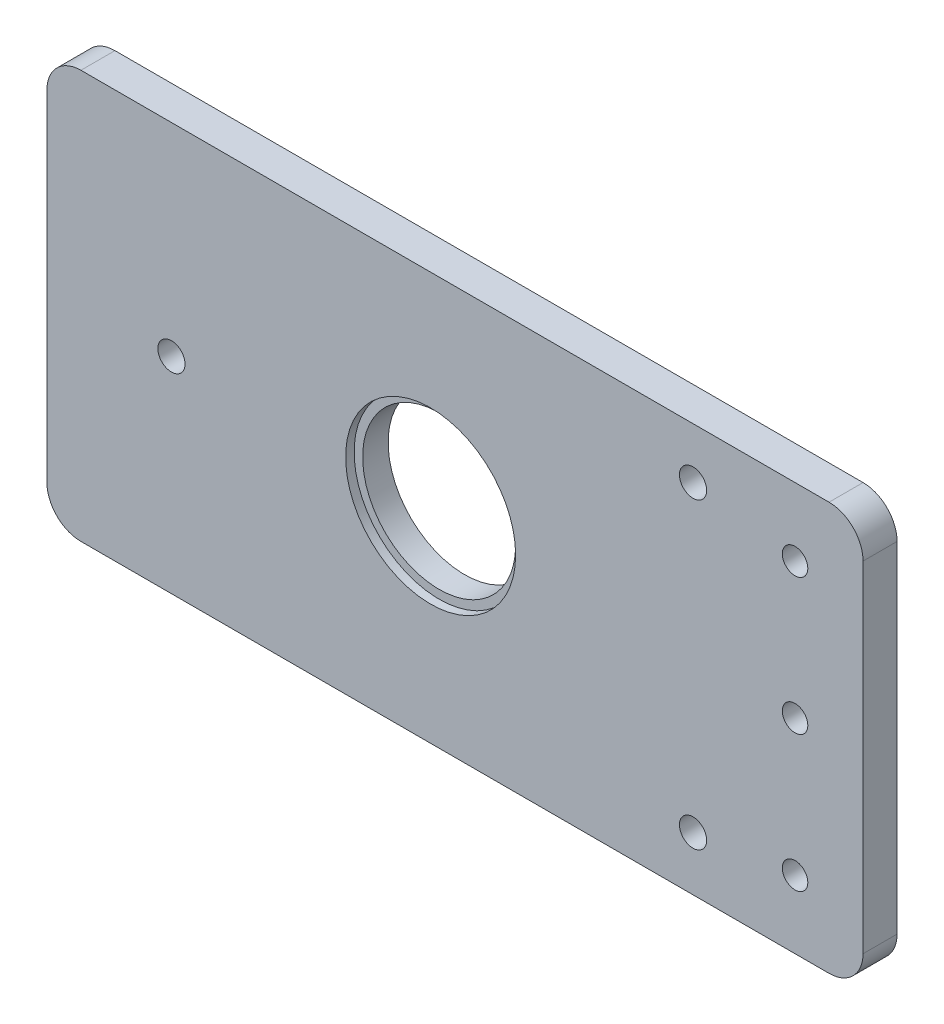
SolidWorks part; units mm, degrees
material "6061-T6 (SS)"
ref_plane "Front" through (0, 0, 0) normal (0, 0, 1) x (1, 0, 0)
ref_plane "Top" through (0, 0, 0) normal (0, 1, 0) x (1, 0, 0)
ref_plane "Right" through (0, 0, 0) normal (1, 0, 0) x (0, 0, -1)
sketch "Sketch1" plane through (0, 0, 0) normal (0, 0, 1) x (1, 0, 0)
  line L1 (-76.2, -38.1) -> (76.2, -38.1)
  line L2 (-76.2, -38.1) -> (-76.2, 38.1)
  line L3 (-76.2, 38.1) -> (76.2, 38.1)
  line L4 (76.2, -38.1) -> (76.2, 38.1)
  line L5 (-76.2, -38.1) -> (76.2, 38.1) construction
  line L6 (-76.2, 38.1) -> (76.2, -38.1) construction
  circle A0 centre (44.45, 28.575) radius 2.54
  circle A1 centre (44.45, -28.0223) radius 2.54
  circle A2 centre (63.5, 25.4) radius 2.3813
  circle A3 centre (63.5, 0) radius 2.3813
  circle A4 centre (63.5, -25.4) radius 2.3813
  circle A5 centre (-4.55, 0.285) radius 14.2875
  circle A6 centre (-52.95, 0.285) radius 2.54
  point P0 (0, 0)
  dimension "D3" = 5.08
  dimension "D7" = 4.7625
  dimension "D10" = 12.7
  dimension "D11" = 28.575
  dimension "D12" = 5.08
  dimension "D1" = 76.2
  dimension "D2" = 152.4
  dimension "D4" = 56.5973
  dimension "D5" = 9.525
  dimension "D6" = 31.75
  dimension "D8" = 12.7
  dimension "D9" = 12.7
  dimension "D13" = 28.29
  dimension "D14" = 49
  dimension "D15" = 97.4
extrude "Boss-Extrude1" add sketch "Sketch1" along normal blind 6.35
fillet "Fillet1" radius 6.35 4 edges at (76.2, -38.1, 3.175) (-76.2, -38.1, 3.175) (76.2, 38.1, 3.175) (-76.2, 38.1, 3.175)
sketch "Sketch2" plane through (0, 0, 6.35) normal (0, 0, 1) x (1, 0, 0)
  circle A0 centre (-4.55, 0.285) radius 15.875
  dimension "D1" = 31.75
extrude "Cut-Extrude1" cut sketch "Sketch2" against normal blind 1.5875
